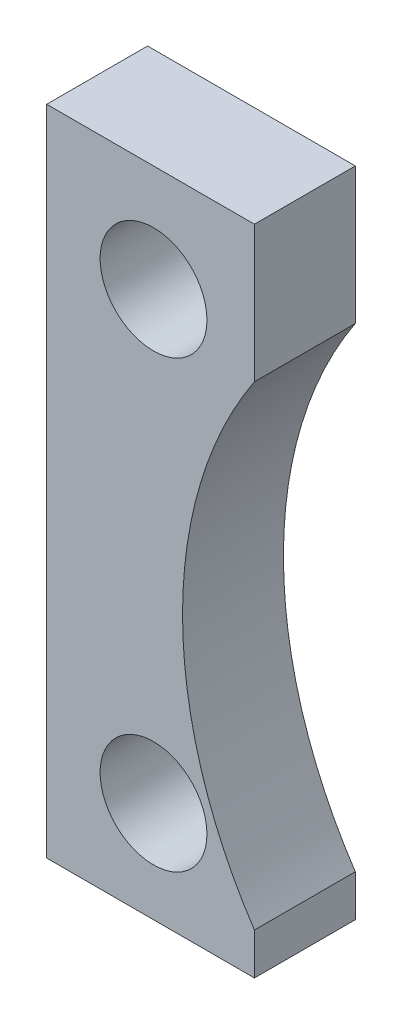
SolidWorks part; units mm, degrees
ref_plane "Ön Düzlem" through (0, 0, 0) normal (0, 0, 1) x (1, 0, 0)
ref_plane "Üst Düzlem" through (0, 0, 0) normal (0, 1, 0) x (1, 0, 0)
ref_plane "Sağ Düzlem" through (0, 0, 0) normal (1, 0, 0) x (0, 0, -1)
sketch "Sketch1" plane through (0, 0, 0) normal (0, 0, 1) x (1, 0, 0)
  line L0 (0, 110) -> (35, 110)
  line L1 (0, 110) -> (0, 0)
  line L2 (0, 0) -> (35, 0)
  line L3 (35, 110) -> (35, 87)
  line L4 (35, 7) -> (35, 0)
  arc A0 (35, 87) -> (35, 7) centre (95, 47) ccw
  dimension "D1" = 110
  dimension "D2" = 35
  dimension "D3" = 7
  dimension "D4" = 23
  dimension "D5" = 95
extrude "Boss-Extrude1" add sketch "Sketch1" along normal mid plane 17
sketch "Sketch2" plane through (0, 0, 8.5) normal (0, 0, 1) x (1, 0, 0)
  line L0 (0, 110) -> (0, 0) construction
  circle A0 centre (18, 92) radius 9
  circle A1 centre (18, 17) radius 9
  dimension "D2" = 18
  dimension "D1" = 75
  dimension "D3" = 18
extrude "Cut-Extrude1" cut sketch "Sketch2" against normal through all
